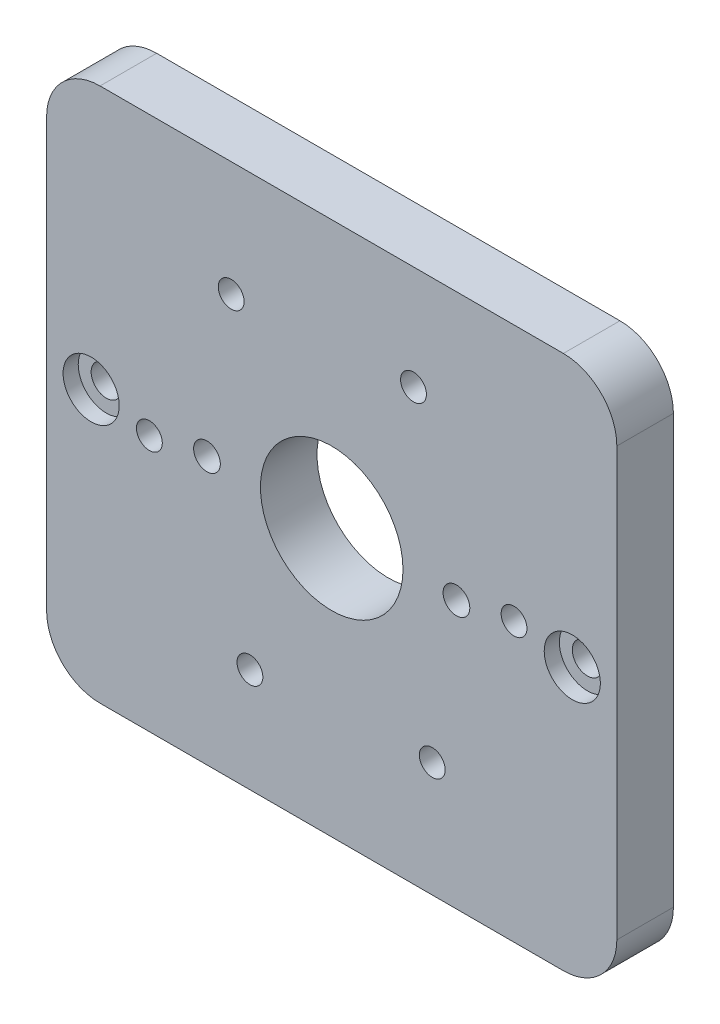
SolidWorks part; units mm, degrees
material "Aleación 6061"
ref_plane "Alzado" through (0, 0, 0) normal (0, 0, 1) x (1, 0, 0)
ref_plane "Planta" through (0, 0, 0) normal (0, 1, 0) x (1, 0, 0)
ref_plane "Vista lateral" through (0, 0, 0) normal (1, 0, 0) x (0, 0, -1)
sketch "Croquis1" plane through (0, 0, 0) normal (0, 0, 1) x (1, 0, 0)
  line L0 (126.4, -30) -> (178.4, -30)
  line L1 (184.4, -24) -> (184.4, 24)
  line L2 (178.4, 30) -> (126.4, 30)
  line L3 (120.4, 24) -> (120.4, -24)
  arc A0 (178.4, -30) -> (184.4, -24) centre (178.4, -24) ccw
  arc A1 (184.4, 24) -> (178.4, 30) centre (178.4, 24) ccw
  arc A2 (126.4, 30) -> (120.4, 24) centre (126.4, 24) ccw
  arc A3 (120.4, -24) -> (126.4, -30) centre (126.4, -24) ccw
  dimension "D1" = 6
  dimension "D2" = 6
  dimension "D3" = 6
  dimension "D4" = 6
  dimension "D5" = 126.4
  dimension "D6" = 30
  dimension "D7" = 178.4
  dimension "D8" = 30
  dimension "D9" = 184.4
  dimension "D10" = 24
  dimension "D11" = 184.4
  dimension "D12" = 24
  dimension "D13" = 178.4
  dimension "D14" = 30
  dimension "D15" = 126.4
  dimension "D16" = 30
  dimension "D17" = 120.4
  dimension "D18" = 24
  dimension "D19" = 120.4
  dimension "D20" = 24
extrude "Repisa_M4" add sketch "Croquis1" along normal blind 6.35 from offset 222.25
sketch "Croquis2" plane through (0, 0, 0) normal (0, 0, 1) x (1, 0, 0)
  circle A0 centre (172.8639, 1.2158) radius 1.45
  circle A1 centre (161.5791, 18.3302) radius 1.45
  circle A2 centre (141.1151, 17.1144) radius 1.45
  circle A3 centre (131.9361, -1.2158) radius 1.45
  circle A4 centre (143.2209, -18.3302) radius 1.45
  circle A5 centre (163.6849, -17.1144) radius 1.45
  circle A6 centre (152.4, 0) radius 8
  circle A7 centre (125.4, 0) radius 1.7
  circle A8 centre (179.4, 0) radius 1.7
  circle A9 centre (138.4, 0) radius 1.5
  circle A10 centre (166.4, 0) radius 1.5
  dimension "D1" = 2.9
  dimension "D2" = 2.9
  dimension "D3" = 2.9
  dimension "D4" = 2.9
  dimension "D5" = 2.9
  dimension "D6" = 2.9
  dimension "D7" = 16
  dimension "D8" = 3.4
  dimension "D9" = 3.4
  dimension "D10" = 3
  dimension "D11" = 3
  dimension "D12" = 172.8639
  dimension "D13" = 1.2158
  dimension "D14" = 161.5791
  dimension "D15" = 18.3302
  dimension "D16" = 141.1151
  dimension "D17" = 17.1144
  dimension "D18" = 131.9361
  dimension "D19" = 1.2158
  dimension "D20" = 143.2209
  dimension "D21" = 18.3302
  dimension "D22" = 163.6849
  dimension "D23" = 17.1144
  dimension "D24" = 152.4
  dimension "D25" = 125.4
  dimension "D26" = 179.4
  dimension "D27" = 138.4
  dimension "D28" = 166.4
extrude "Barrenos_M4_tornillos_pasadores" cut sketch "Croquis2" along normal blind 6.35 from offset 222.25
sketch "Croquis3" plane through (0, 0, 0) normal (0, 0, 1) x (1, 0, 0)
  circle A0 centre (172.8639, 1.2158) radius 2.5
  circle A1 centre (161.5791, 18.3302) radius 2.5
  circle A2 centre (141.1151, 17.1144) radius 2.5
  circle A3 centre (131.9361, -1.2158) radius 2.5
  circle A4 centre (143.2209, -18.3302) radius 2.5
  circle A5 centre (163.6849, -17.1144) radius 2.5
  dimension "D1" = 5
  dimension "D2" = 5
  dimension "D3" = 5
  dimension "D4" = 5
  dimension "D5" = 5
  dimension "D6" = 5
  dimension "D7" = 172.8639
  dimension "D8" = 1.2158
  dimension "D9" = 161.5791
  dimension "D10" = 18.3302
  dimension "D11" = 141.1151
  dimension "D12" = 17.1144
  dimension "D13" = 131.9361
  dimension "D14" = 1.2158
  dimension "D15" = 143.2209
  dimension "D16" = 18.3302
  dimension "D17" = 163.6849
  dimension "D18" = 17.1144
extrude "Refrentado_M2-5" cut sketch "Croquis3" along normal blind 2.6 from offset 222.25
sketch "Croquis4" plane through (0, 0, 0) normal (0, 0, 1) x (1, 0, 0)
  circle A0 centre (125.4, 0) radius 3.15
  circle A1 centre (179.4, 0) radius 3.15
  dimension "D1" = 6.3
  dimension "D2" = 6.3
  dimension "D3" = 125.4
  dimension "D4" = 179.4
extrude "Avellanado_M3" cut sketch "Croquis4" along normal blind 1.7 from offset 226.9
